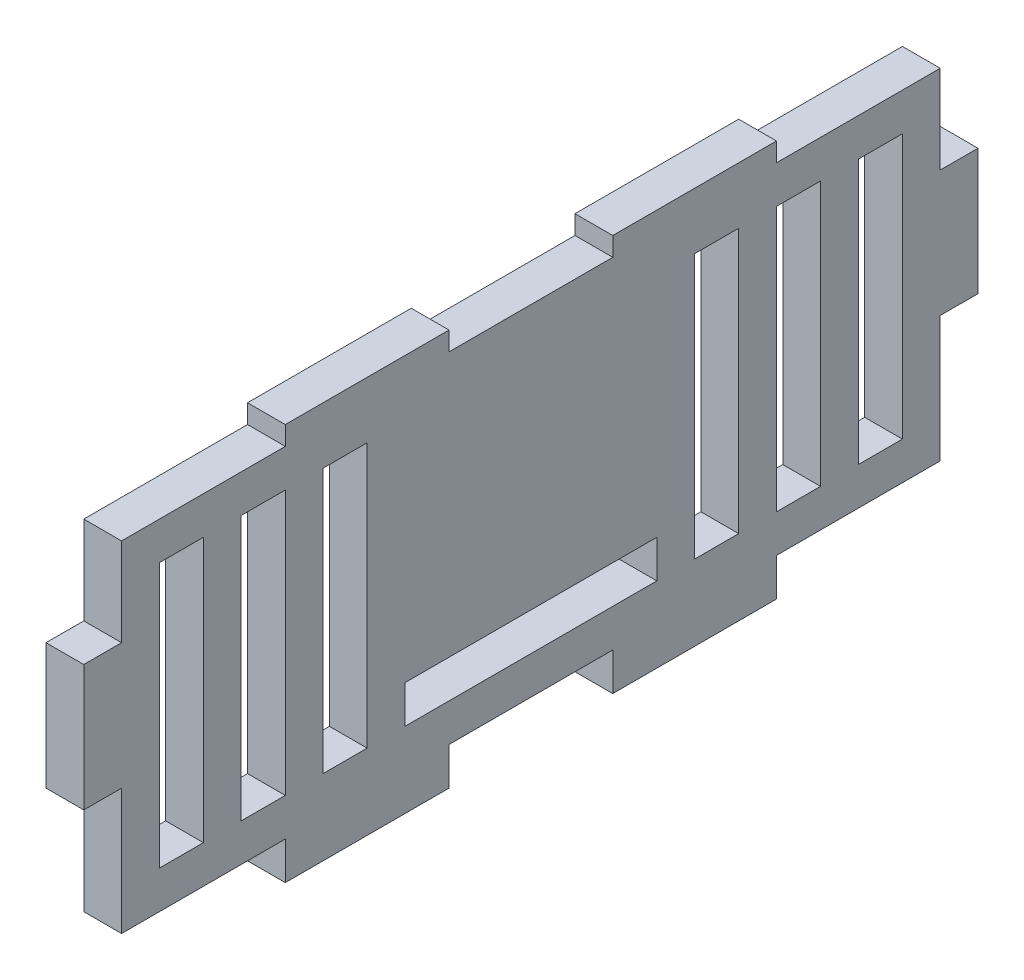
SolidWorks part; units mm, degrees
ref_plane "Front Plane" through (0, 0, 0) normal (0, 0, 1) x (1, 0, 0)
ref_plane "Top Plane" through (0, 0, 0) normal (0, 1, 0) x (1, 0, 0)
ref_plane "Right Plane" through (0, 0, 0) normal (1, 0, 0) x (0, 0, -1)
sketch "Sketch1" plane through (0, 0, 0) normal (1, 0, 0) x (0, 0, -1)
  line L0 (-46.2469, 21.4205) -> (-20.2469, 21.4205)
  line L2 (-46.2469, 21.4205) -> (-46.2469, 7.4205)
  line L3 (-46.2469, -32.5795) -> (-20.2469, -32.5795)
  line L4 (83.7531, 21.4205) -> (83.7531, 7.4205)
  line L5 (5.7531, 21.4205) -> (31.7531, 21.4205)
  line L6 (-20.2469, -32.5795) -> (-20.2469, -38.5795)
  line L7 (-20.2469, -38.5795) -> (5.7531, -38.5795)
  line L8 (5.7531, -38.5795) -> (5.7531, -32.5795)
  line L9 (31.7531, -32.5795) -> (31.7531, -38.5795)
  line L10 (31.7531, -38.5795) -> (57.7531, -38.5795)
  line L11 (57.7531, -38.5795) -> (57.7531, -32.5795)
  line L12 (5.7531, -32.5795) -> (31.7531, -32.5795)
  line L13 (57.7531, -32.5795) -> (83.7531, -32.5795)
  line L14 (-46.2469, -12.5795) -> (-52.2469, -12.5795)
  line L15 (-52.2469, -12.5795) -> (-52.2469, 7.4205)
  line L16 (-52.2469, 7.4205) -> (-46.2469, 7.4205)
  line L17 (83.7531, 7.4205) -> (89.7531, 7.4205)
  line L18 (89.7531, 7.4205) -> (89.7531, -12.5795)
  line L19 (89.7531, -12.5795) -> (83.7531, -12.5795)
  line L20 (-46.2469, -12.5795) -> (-46.2469, -32.5795)
  line L21 (83.7531, -12.5795) -> (83.7531, -32.5795)
  line L22 (57.7531, 24.4205) -> (57.7531, 21.4205)
  line L23 (31.7531, 24.4205) -> (57.7531, 24.4205)
  line L24 (31.7531, 21.4205) -> (31.7531, 24.4205)
  line L25 (5.7531, 24.4205) -> (5.7531, 21.4205)
  line L26 (-20.2469, 24.4205) -> (5.7531, 24.4205)
  line L27 (-20.2469, 21.4205) -> (-20.2469, 24.4205)
  line L28 (57.7531, 21.4205) -> (83.7531, 21.4205)
  line L29 (18.7531, 21.4205) -> (18.7531, -32.5795) construction
  line L35 (18.7531, 3.4205) -> (18.7531, -14.5795) construction
  line L36 (18.7531, 3.4205) -> (18.7531, 21.4205) construction
  line L38 (-40.2469, 15.4205) -> (-33.2469, 15.4205)
  line L39 (-40.2469, 15.4205) -> (-40.2469, -26.5795)
  line L40 (-40.2469, -26.5795) -> (-33.2469, -26.5795)
  line L41 (-33.2469, 15.4205) -> (-33.2469, -26.5795)
  line L45 (51.7531, 15.4205) -> (51.7531, -26.5795)
  line L46 (-27.2469, 15.4205) -> (-20.2469, 15.4205)
  line L47 (-27.2469, 15.4205) -> (-27.2469, -26.5795)
  line L48 (-27.2469, -26.5795) -> (-20.2469, -26.5795)
  line L49 (-20.2469, 15.4205) -> (-20.2469, -26.5795)
  line L50 (-14.2469, 15.4205) -> (-7.2469, 15.4205)
  line L51 (-14.2469, 15.4205) -> (-14.2469, -26.5795)
  line L52 (-14.2469, -26.5795) -> (-7.2469, -26.5795)
  line L53 (-7.2469, 15.4205) -> (-7.2469, -26.5795)
  line L58 (-1.2469, -26.5795) -> (38.7531, -26.5795)
  line L59 (-1.2469, -26.5795) -> (-1.2469, -20.5795)
  line L60 (-1.2469, -20.5795) -> (38.7531, -20.5795)
  line L61 (38.7531, -26.5795) -> (38.7531, -20.5795)
  line L62 (51.7531, -26.5795) -> (44.7531, -26.5795)
  line L63 (44.7531, 15.4205) -> (44.7531, -26.5795)
  line L64 (51.7531, 15.4205) -> (44.7531, 15.4205)
  line L65 (64.7531, 15.4205) -> (64.7531, -26.5795)
  line L66 (64.7531, -26.5795) -> (57.7531, -26.5795)
  line L67 (57.7531, 15.4205) -> (57.7531, -26.5795)
  line L68 (64.7531, 15.4205) -> (57.7531, 15.4205)
  line L69 (77.7531, -26.5795) -> (70.7531, -26.5795)
  line L70 (70.7531, 15.4205) -> (70.7531, -26.5795)
  line L71 (77.7531, 15.4205) -> (70.7531, 15.4205)
  line L72 (77.7531, 15.4205) -> (77.7531, -26.5795)
  point P4 (-1.2469, -23.5795)
  dimension "D1" = 26
  dimension "D2" = 54
  dimension "D3" = 6
  dimension "D4" = 6
  dimension "D5" = 26
  dimension "D6" = 26
  dimension "D7" = 26
  dimension "D8" = 26
  dimension "D9" = 6
  dimension "D10" = 20
  dimension "D11" = 20
  dimension "D12" = 20
  dimension "D13" = 20
  dimension "D14" = 26
  dimension "D15" = 26
  dimension "D16" = 26
  dimension "D17" = 3
  dimension "D18" = 26
  dimension "D20" = 6
  dimension "D21" = 3
  dimension "D22" = 3
  dimension "D23" = 26
  dimension "D24" = 14
  dimension "D25" = 18
  dimension "D27" = 6
  dimension "D28" = 6
  dimension "D30" = 7
  dimension "D31" = 6
  dimension "D32" = 6
  dimension "D33" = 6
  dimension "D34" = 7
  dimension "D35" = 6
  dimension "D39" = 40
  dimension "D41" = 6
  dimension "D42" = 6
  dimension "D44" = 6
extrude "Boss-Extrude1" add sketch "Sketch1" along normal blind 6
